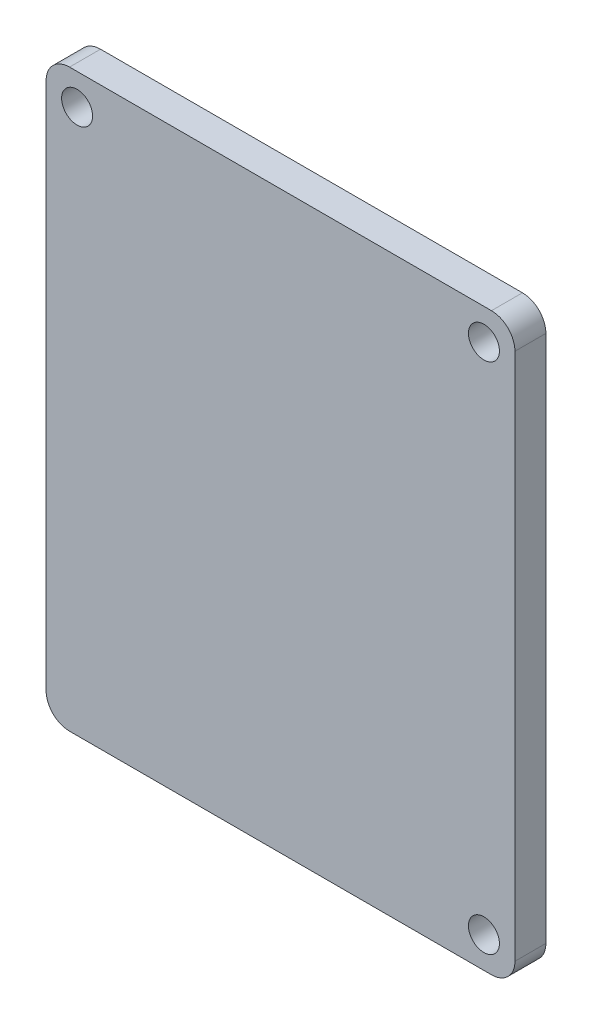
SolidWorks part; units mm, degrees
ref_plane "Front Plane" through (0, 0, 0) normal (0, 0, 1) x (1, 0, 0)
ref_plane "Top Plane" through (0, 0, 0) normal (0, 1, 0) x (1, 0, 0)
ref_plane "Right Plane" through (0, 0, 0) normal (1, 0, 0) x (0, 0, -1)
sketch "Esboço1" plane through (0, 0, 0) normal (0, 0, 1) x (1, 0, 0)
  line L1 (2.2697, 0) -> (43.1303, 0)
  line L2 (0, 2.2697) -> (0, 53.4303)
  line L3 (2.2697, 55.7) -> (43.1303, 55.7)
  line L4 (45.4, 2.2697) -> (45.4, 53.4303)
  arc A0 (2.2697, 55.7) -> (0, 53.4303) centre (2.2697, 53.4303) ccw
  arc A1 (2.2697, 0) -> (0, 2.2697) centre (2.2697, 2.2697) cw
  arc A2 (43.1303, 0) -> (45.4, 2.2697) centre (43.1303, 2.2697) ccw
  arc A3 (45.4, 53.4303) -> (43.1303, 55.7) centre (43.1303, 53.4303) ccw
  circle A9 centre (42.4, 3) radius 1.5
  circle A10 centre (42.4, 52.7) radius 1.5
  circle A11 centre (3, 52.7) radius 1.5
  point P7 (0, 55.7)
  point P10 (0, 0)
  point P13 (45.4, 0)
  point P16 (45.4, 55.7)
  point P25 (0, 0)
  point P27 (41.2149, 52.0953)
  dimension "D3" = 2.2697
  dimension "D4" = 3
  dimension "D7" = 3
  dimension "D15" = 3
  dimension "D1" = 45.4
  dimension "D2" = 55.7
  dimension "D5" = 3
  dimension "D6" = 3
  dimension "D8" = 3
  dimension "D9" = 3
  dimension "D10" = 3
  dimension "D11" = 3
extrude "Ressalto-extrusão1" add sketch "Esboço1" along normal blind 3
equation "\"D7@Esboço1\"=\"D4@Esboço1\""
equation "\"D8@Esboço1\"=\"D5@Esboço1\""
equation "\"D9@Esboço1\"=\"D6@Esboço1\""
equation "\"D10@Esboço1\"=\"D5@Esboço1\""
equation "\"D11@Esboço1\"=\"D6@Esboço1\""
equation "\"D15@Esboço1\"=\"D4@Esboço1\""
